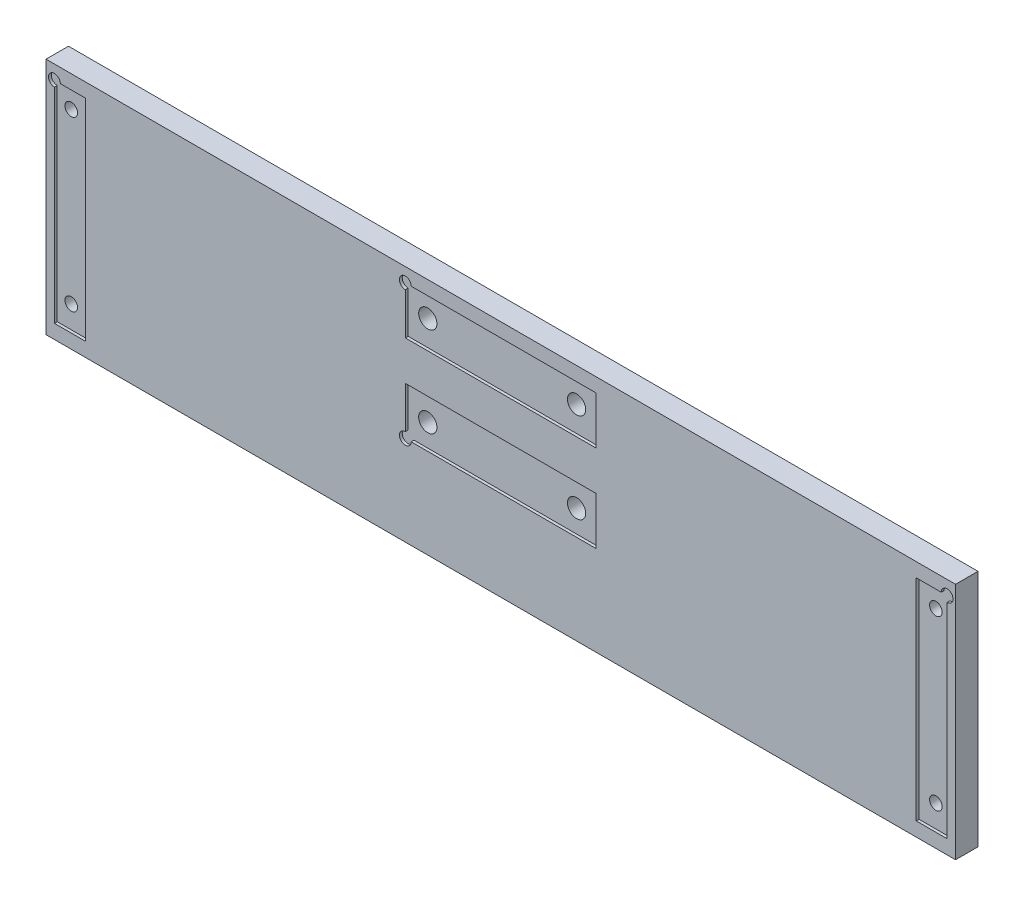
SolidWorks part; units mm, degrees
ref_plane "Plan de face" through (0, 0, 0) normal (0, 0, 1) x (1, 0, 0)
ref_plane "Plan de dessus" through (0, 0, 0) normal (0, 1, 0) x (1, 0, 0)
ref_plane "Plan de droite" through (0, 0, 0) normal (1, 0, 0) x (0, 0, -1)
sketch "Esquisse1" plane through (0, 0, 0) normal (0, 0, 1) x (1, 0, 0)
  line L0 (0, 100.453) -> (0, -98.9703) construction
  line L2 (-162, 42.5) -> (162, 42.5)
  line L3 (-162, 42.5) -> (-162, -42.5)
  line L4 (-162, -42.5) -> (162, -42.5)
  line L5 (162, 42.5) -> (162, -42.5)
  line L6 (-162, 42.5) -> (162, -42.5) construction
  line L7 (-162, -42.5) -> (162, 42.5) construction
  point P3 (0, 0)
  dimension "D1" = 324
  dimension "D2" = 85
extrude "Boss.-Extru.1" add sketch "Esquisse1" along normal blind 8
sketch "Esquisse2" plane through (0, 0, 8) normal (0, 0, 1) x (1, 0, 0)
  line L0 (162, 42.5) -> (-162, 42.5) construction
  line L1 (148, 37.5) -> (156.9, 37.5)
  line L2 (148, 37.5) -> (148, -37.5)
  line L3 (148, -37.5) -> (159, -37.5)
  line L4 (159, 35.4) -> (159, -37.5)
  line L5 (148, 37.5) -> (159, -37.5) construction
  line L6 (148, -37.5) -> (159, 37.5) construction
  line L7 (162, -42.5) -> (162, 42.5) construction
  arc A0 (156.9, 37.5) -> (159, 35.4) centre (159, 37.5) cw
  point P0 (153.5, 0)
  dimension "D5" = 2.1
  dimension "D1" = 75
  dimension "D2" = 11
  dimension "D4" = 3
  dimension "D7" = 5
extrude "Enlèv. mat.-Extru.1" cut sketch "Esquisse2" against normal blind 1
mirror "Symétrie1" about plane through (0, 0, 0) normal (1, 0, 0) of "Enlèv. mat.-Extru.1"
sketch "Esquisse3" plane through (0, 0, 7) normal (0, 0, 1) x (1, 0, 0)
  line L0 (233.6964, 0.5) -> (192.1403, 0.5) construction
  line L1 (156.9, 37.5) -> (148, 37.5) construction
  line L2 (159, -37.5) -> (159, 35.4) construction
  circle A0 centre (154, 30.5) radius 2.25
  circle A1 centre (154, -29.5) radius 2.25
  dimension "D3" = 4.5
  dimension "D1" = 7
  dimension "D2" = 5
  dimension "D4" = 30
extrude "Enlèv. mat.-Extru.2" cut sketch "Esquisse3" against normal through all
mirror "Symétrie2" about plane through (0, 0, 0) normal (1, 0, 0) of "Enlèv. mat.-Extru.2"
sketch "Esquisse4" plane through (0, 0, 8) normal (0, 0, 1) x (1, 0, 0)
  line L0 (0, 11.5039) -> (0, 55.69) construction
  line L1 (-31.9, 37.5) -> (34, 37.5)
  line L2 (-34, 35.4) -> (-34, 20.5)
  line L3 (-34, 20.5) -> (34, 20.5)
  line L4 (34, 37.5) -> (34, 20.5)
  line L5 (-34, 37.5) -> (34, 20.5) construction
  line L6 (-34, 20.5) -> (34, 37.5) construction
  line L7 (162, 42.5) -> (-162, 42.5) construction
  line L8 (-40.9309, 13.5) -> (56.3141, 13.5) construction
  line L9 (-34, 6.5) -> (34, -10.5) construction
  line L10 (-34, -10.5) -> (34, 6.5) construction
  line L19 (34, -10.5) -> (34, 6.5)
  line L20 (-34, 6.5) -> (34, 6.5)
  line L21 (-34, -8.4) -> (-34, 6.5)
  line L22 (-31.9, -10.5) -> (34, -10.5)
  arc A2 (-31.9, 37.5) -> (-34, 35.4) centre (-34, 37.5) ccw
  arc A3 (-31.9, -10.5) -> (-34, -8.4) centre (-34, -10.5) cw
  point P0 (0, 29)
  point P20 (0, -2)
  dimension "D5" = 2.1
  dimension "D1" = 68
  dimension "D2" = 17
  dimension "D3" = 5
  dimension "D4" = 7
extrude "Enlèv. mat.-Extru.3" cut sketch "Esquisse4" against normal blind 1
sketch "Esquisse5" plane through (0, 0, 7) normal (0, 0, 1) x (1, 0, 0)
  line L0 (-0.5, 43.9553) -> (-0.5, 15.1111) construction
  line L1 (34, 37.5) -> (-31.9, 37.5) construction
  line L2 (-37.557, 13.5) -> (44.5617, 13.5) construction
  line L5 (-34, 35.4) -> (-34, 20.5) construction
  circle A0 centre (-27, 29.5) radius 3.25
  circle A1 centre (26, 29.5) radius 3.25
  circle A2 centre (26, -2.5) radius 3.25
  circle A3 centre (-27, -2.5) radius 3.25
  dimension "D3" = 6.5
  dimension "D1" = 26.5
  dimension "D2" = 8
  dimension "D4" = 7
  dimension "D5" = 33.5
extrude "Enlèv. mat.-Extru.4" cut sketch "Esquisse5" against normal through all
